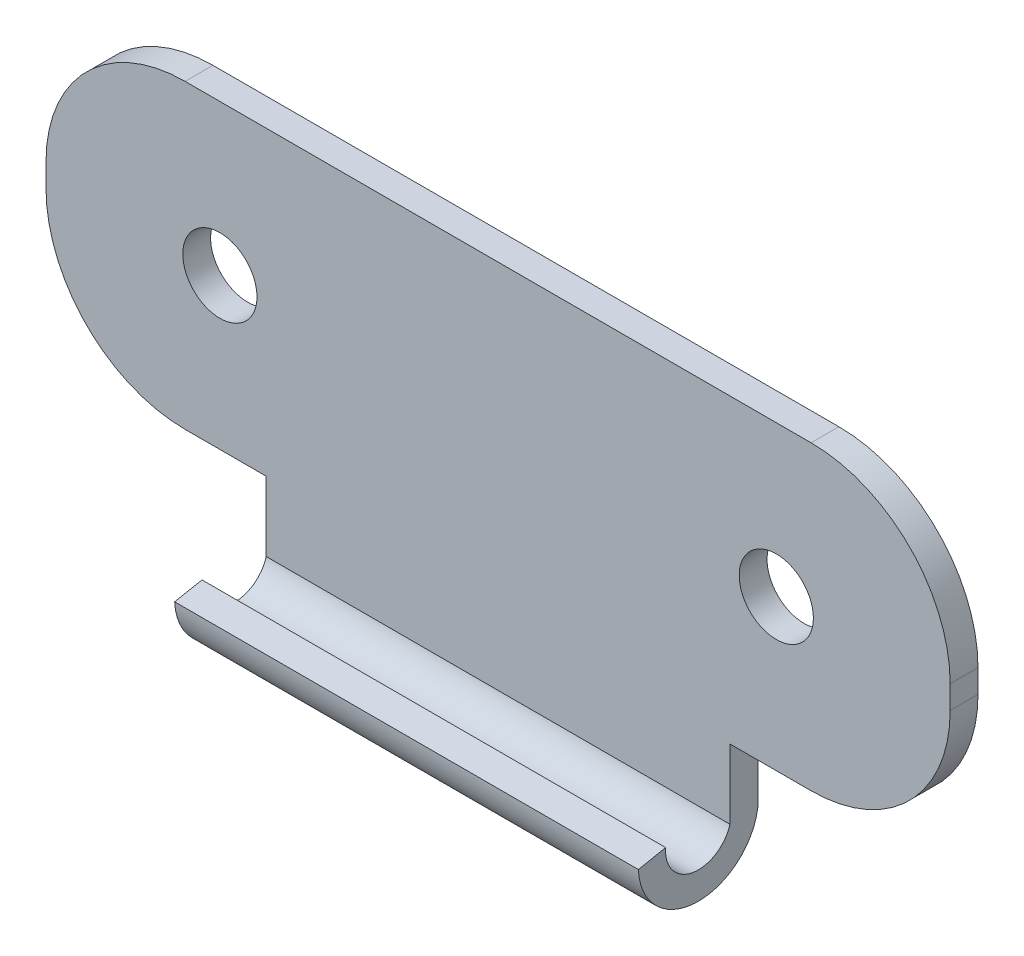
SolidWorks part; units mm, degrees
ref_plane "前视基准面" through (0, 0, 0) normal (0, 0, 1) x (1, 0, 0)
ref_plane "上视基准面" through (0, 0, 0) normal (0, 1, 0) x (1, 0, 0)
ref_plane "右视基准面" through (0, 0, 0) normal (1, 0, 0) x (0, 0, -1)
sketch "草图1" plane through (0, 0, 0) normal (0, 0, 1) x (1, 0, 0)
  line L0 (7.4781, -4.5785) -> (10.9781, -4.5785)
  line L1 (-16.0219, 8.4215) -> (10.9781, 8.4215)
  line L2 (-22.0219, 2.4215) -> (-22.0219, 1.4215)
  line L3 (-16.0219, -4.5785) -> (-12.5219, -4.5785)
  line L4 (16.9781, 2.4215) -> (16.9781, 1.4215)
  line L6 (-12.5219, -4.5785) -> (-12.5219, -7.5785)
  line L7 (-12.5219, -7.5785) -> (7.4781, -7.5785)
  line L8 (7.4781, -4.5785) -> (7.4781, -7.5785)
  arc A0 (16.9781, 2.4215) -> (10.9781, 8.4215) centre (10.9781, 2.4215) ccw
  arc A1 (-22.0219, 2.4215) -> (-16.0219, 8.4215) centre (-16.0219, 2.4215) cw
  arc A2 (16.9781, 1.4215) -> (10.9781, -4.5785) centre (10.9781, 1.4215) cw
  arc A3 (-16.0219, -4.5785) -> (-22.0219, 1.4215) centre (-16.0219, 1.4215) cw
  point P6 (16.9781, 8.4215)
  point P9 (-22.0219, 8.4215)
  point P14 (-22.0219, -4.5785)
  dimension "D3" = 6
  dimension "D4" = 6
  dimension "D1" = 39
  dimension "D2" = 13
  dimension "D5" = 3
  dimension "D6" = 20
  dimension "D7" = 9.5
extrude "凸台-拉伸1" add sketch "草图1" along normal blind 1.2
sketch "草图2" plane through (0, 0, 1.2) normal (0, 0, 1) x (1, 0, 0)
  line L0 (-22.0219, 2.4215) -> (-22.0219, 1.4215) construction
  line L1 (10.9781, 8.4215) -> (-16.0219, 8.4215) construction
  circle A0 centre (-14.5219, 1.9215) radius 1.6
  circle A1 centre (9.4781, 1.9215) radius 1.6
  dimension "D1" = 24
  dimension "D2" = 7.5
  dimension "D3" = 6.5
  dimension "D5" = 3.2
  dimension "D6" = 3.2
  dimension "D4" = 6.5
extrude "切除-拉伸1" cut sketch "草图2" against normal blind 1.2
sketch "草图3" plane through (-12.5219, 0, 0) normal (-1, 0, 0) x (0, 0, 1)
  line L1 (1.2, -7.5785) -> (0, -7.5785) construction
  arc A0 (0.6, -7.5785) -> (4.5611, -7.1787) centre (2.5612, -7.1863) ccw
  dimension "D1" = 2
sketch "草图4" plane through (0, -7.5785, 0) normal (0, -1, 0) x (1, 0, 0)
  line L1 (-12.5219, 1.2) -> (7.4781, 1.2)
  line L2 (-12.5219, 1.2) -> (-12.5219, 0)
  line L3 (-12.5219, 0) -> (7.4781, 0)
  line L4 (7.4781, 1.2) -> (7.4781, 0)
sweep "扫描1" add profiles "草图4" path "草图3"
